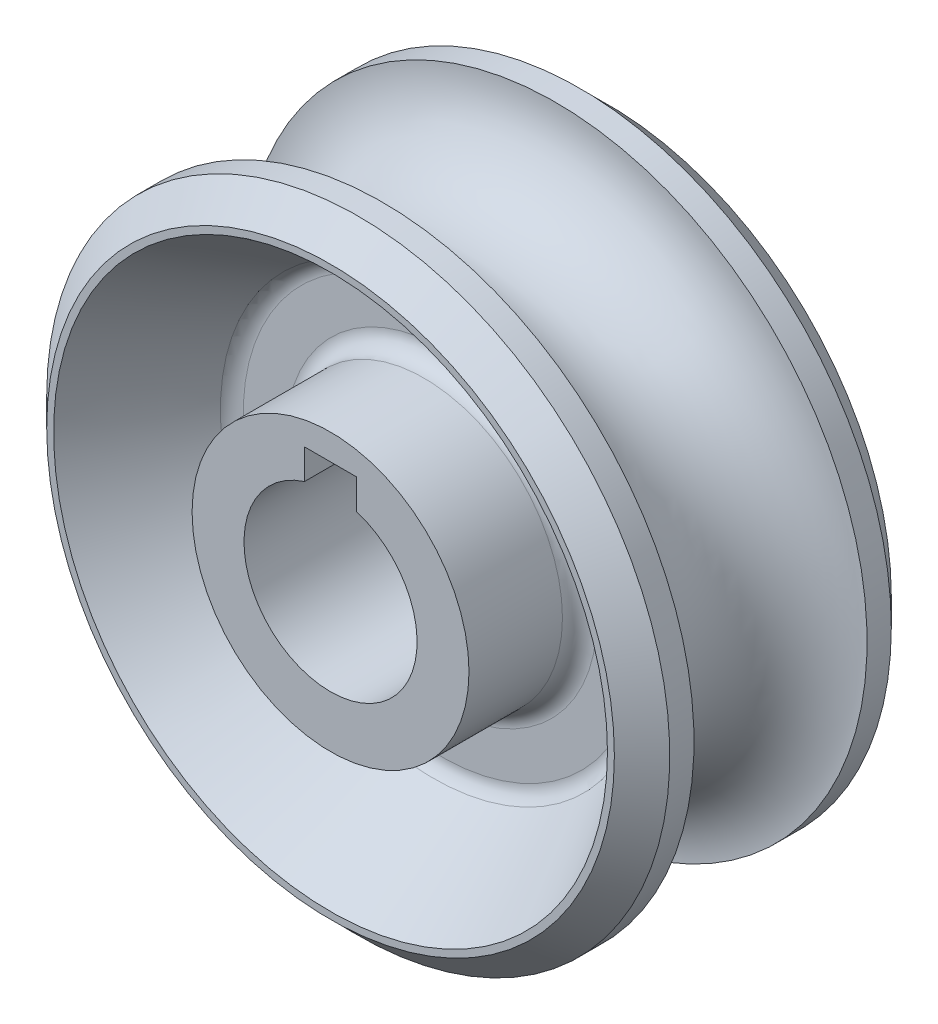
SolidWorks part; units mm, degrees
material "AISI 1020"
ref_plane "Front Plane" through (0, 0, 0) normal (0, 0, 1) x (1, 0, 0)
ref_plane "Top Plane" through (0, 0, 0) normal (0, 1, 0) x (1, 0, 0)
ref_plane "Right Plane" through (0, 0, 0) normal (1, 0, 0) x (0, 0, -1)
sketch "Sketch1" plane through (0, 0, 0) normal (0, 0, 1) x (1, 0, 0)
  circle A0 centre (0, 0) radius 28.575
  circle A1 centre (0, 0) radius 7.9375
  dimension "D1" = 57.15
  dimension "D2" = 15.875
extrude "Base" add sketch "Sketch1" along normal mid plane 25.4
sketch "Sketch2" plane through (0, 0, 0) normal (1, 0, 0) x (0, 0, -1)
  line L0 (12.7, 28.575) -> (-12.7, 28.575) construction
  line L1 (0, 0) -> (19.2227, 0) construction
  circle A0 centre (0, 28.575) radius 7.9375
  dimension "D1" = 15.875
revolve "Groove" cut sketch "Sketch2" angle 360 about L1
sketch "Sketch3" plane through (0, 0, 0) normal (1, 0, 0) x (0, 0, -1)
  line L0 (12.7, 25.4) -> (12.7, 12.7)
  line L1 (12.7, -28.575) -> (12.7, 28.575) construction
  line L2 (12.7, 12.7) -> (2.54, 12.7)
  line L3 (2.54, 12.7) -> (2.54, 19.05)
  line L4 (2.54, 19.05) -> (12.7, 25.4)
  line L5 (0, 0) -> (20.4123, 0) construction
  line L6 (0, 0) -> (0, 31.3003) construction
  line L7 (-2.54, 12.7) -> (-2.54, 19.05)
  line L8 (-12.7, 12.7) -> (-2.54, 12.7)
  line L9 (-12.7, 25.4) -> (-12.7, 12.7)
  line L10 (-2.54, 19.05) -> (-12.7, 25.4)
  dimension "D1" = 10.16
  dimension "D2" = 6.35
  dimension "D3" = 50.8
  dimension "D4" = 25.4
revolve "Cut-Revolve2" cut sketch "Sketch3" angle 360 about L5
chamfer "Chamfer1" distance 2.54 angle 45 2 edges at (28.575, 0, 12.7) (28.575, 0, -12.7)
fillet "Fillet1" radius 1.5875 4 edges at (19.05, 0, -2.54) (12.7, 0, -2.54) (12.7, 0, 2.54) (19.05, 0, 2.54)
sketch "Sketch4" plane through (0, 0, 0) normal (0, 0, 1) x (1, 0, 0)
  line L1 (-2.3876, 10.3251) -> (2.3876, 10.3251)
  line L2 (-2.3876, 10.3251) -> (-2.3876, 0)
  line L3 (-2.3876, 0) -> (2.3876, 0)
  line L4 (2.3876, 10.3251) -> (2.3876, 0)
  circle A5 centre (0, 0) radius 7.9375 construction
  dimension "D2" = 2.3876
  dimension "D1" = 4.7752
extrude "Keyway" cut sketch "Sketch4" against normal through all both and the other way through all
